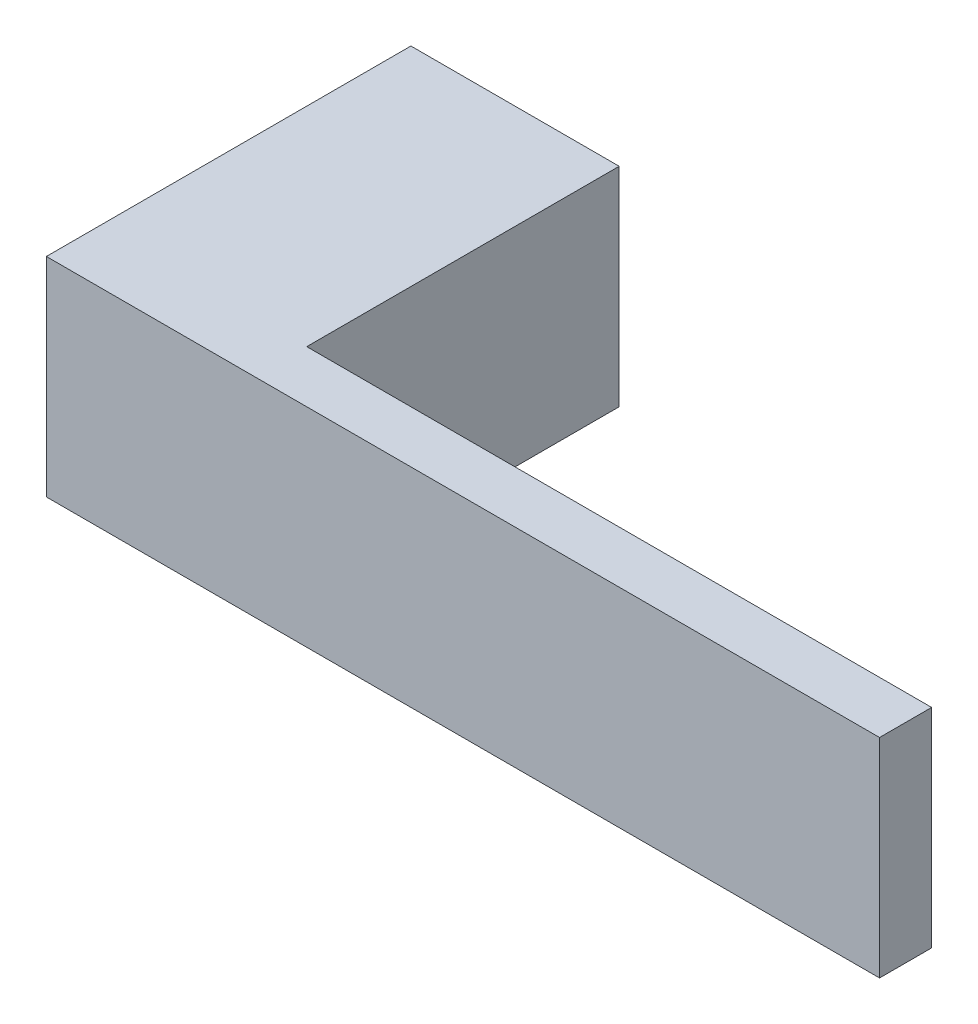
SolidWorks part; units mm, degrees
ref_plane "Přední rovina" through (0, 0, 0) normal (0, 0, 1) x (1, 0, 0)
ref_plane "Horní rovina" through (0, 0, 0) normal (0, 1, 0) x (1, 0, 0)
ref_plane "Pravá rovina" through (0, 0, 0) normal (1, 0, 0) x (0, 0, -1)
sketch "Sketch2" plane through (0, 0, 0) normal (0, 1, 0) x (1, 0, 0)
  line L0 (0, -35) -> (0, 0)
  line L1 (80, -35) -> (0, -35)
  line L2 (80, -35) -> (80, -30)
  line L3 (80, -30) -> (20, -30)
  line L7 (0, 0) -> (20, 0)
  line L8 (20, -30) -> (20, 0)
  dimension "D1" = 80
  dimension "D2" = 5
  dimension "D3" = 30
  dimension "D4" = 20
extrude "Boss-Extrude1" add sketch "Sketch2" along normal blind 20
